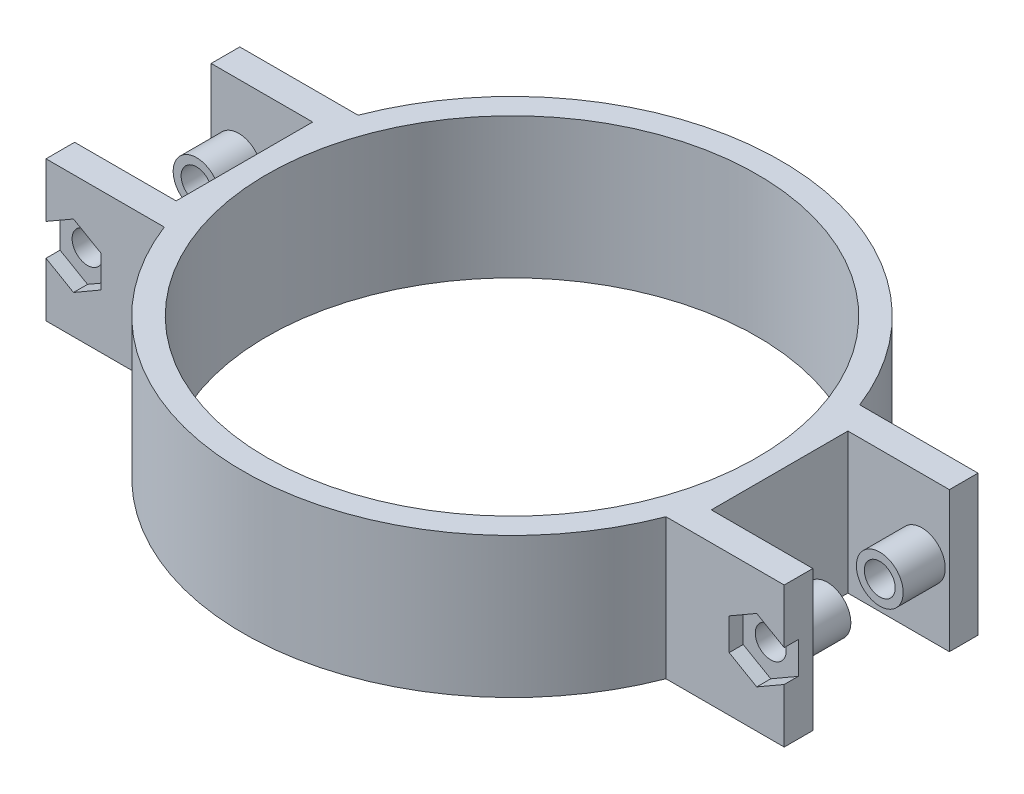
SolidWorks part; units mm, degrees
ref_plane "前视基准面" through (0, 0, 0) normal (0, 0, 1) x (1, 0, 0)
ref_plane "上视基准面" through (0, 0, 0) normal (0, 1, 0) x (1, 0, 0)
ref_plane "右视基准面" through (0, 0, 0) normal (1, 0, 0) x (0, 0, -1)
sketch "草图1" plane through (0, 0, 0) normal (0, 1, 0) x (1, 0, 0)
  line L0 (-39.4388, 7.2962) -> (-28.5931, 7.2962)
  line L1 (-26.8011, -10.3527) -> (-39.4388, -10.3527)
  line L2 (-28.5931, 7.2962) -> (-28.5931, -7.2962)
  line L3 (-26.8011, 10.3527) -> (-39.4388, 10.3527)
  line L4 (-39.4388, -10.3527) -> (-39.4388, -7.2962)
  line L5 (-28.5931, -7.2962) -> (-39.4388, -7.2962)
  line L6 (-39.4388, 7.2962) -> (-39.4388, 10.3527)
  line L7 (26.8011, 10.3527) -> (39.4388, 10.3527)
  line L8 (39.4388, 10.3527) -> (39.4388, 7.2962)
  line L9 (39.4388, -10.3527) -> (26.8011, -10.3527)
  line L10 (39.4388, -7.2962) -> (39.4388, -10.3527)
  line L11 (39.4388, 7.2962) -> (28.5931, 7.2962)
  line L12 (28.5931, 7.2962) -> (28.5931, -7.2962)
  line L13 (28.5931, -7.2962) -> (39.4388, -7.2962)
  circle A0 centre (0, 0) radius 26.2
  arc A2 (-26.8011, -10.3527) -> (26.8011, -10.3527) centre (0, 0) ccw
  arc A3 (26.8011, 10.3527) -> (-26.8011, 10.3527) centre (0, 0) ccw
  dimension "D1" = 52.4
extrude "凸台-拉伸1" add sketch "草图1" along normal blind 15
sketch "草图2" plane through (0, 0, -10.3527) normal (0, 0, -1) x (-1, 0, 0)
  circle A0 centre (36.5, 7.5) radius 1.65
  circle A1 centre (-36.5, 7.5) radius 1.65
extrude "切除-拉伸1" cut sketch "草图2" against normal blind 23
sketch "草图3" plane through (0, 0, 10.3527) normal (0, 0, 1) x (1, 0, 0)
  line L1 (-36.5, 4.1) -> (-33.5555, 5.8)
  line L2 (-33.5555, 5.8) -> (-33.5555, 9.2)
  line L3 (-33.5555, 9.2) -> (-36.5, 10.9)
  line L4 (-36.5, 10.9) -> (-39.4445, 9.2)
  line L5 (-39.4445, 9.2) -> (-39.4445, 5.8)
  line L6 (-39.4445, 5.8) -> (-36.5, 4.1)
  circle A0 centre (-36.5, 7.5) radius 2.9445 construction
  dimension "D1" = 3.4
extrude "切除-拉伸2" cut sketch "草图3" against normal blind 1.5
sketch "草图4" plane through (0, 0, 10.3527) normal (0, 0, 1) x (1, 0, 0)
  line L1 (36.5, 4.1) -> (39.4445, 5.8)
  line L2 (39.4445, 5.8) -> (39.4445, 9.2)
  line L3 (39.4445, 9.2) -> (36.5, 10.9)
  line L4 (36.5, 10.9) -> (33.5555, 9.2)
  line L5 (33.5555, 9.2) -> (33.5555, 5.8)
  line L6 (33.5555, 5.8) -> (36.5, 4.1)
  circle A0 centre (36.5, 7.5) radius 2.9445 construction
  dimension "D1" = 3.4
extrude "切除-拉伸3" cut sketch "草图4" against normal blind 1.5
sketch "草图5" plane through (0, 0, -7.2962) normal (0, 0, 1) x (1, 0, 0)
  circle A0 centre (-36.5, 7.5) radius 2.5
  circle A1 centre (-36.5, 7.5) radius 1.65
  dimension "D1" = 5
extrude "凸台-拉伸2" add sketch "草图5" along normal blind 4.5
sketch "草图6" plane through (0, 0, 7.2962) normal (0, 0, -1) x (-1, 0, 0)
  circle A0 centre (36.5, 7.5) radius 1.65
  circle A1 centre (36.5, 7.5) radius 2.5
  dimension "D1" = 5
extrude "凸台-拉伸3" add sketch "草图6" along normal blind 4.5
sketch "草图7" plane through (0, 0, -7.2962) normal (0, 0, 1) x (1, 0, 0)
  circle A0 centre (36.5, 7.5) radius 1.65
  circle A1 centre (36.5, 7.5) radius 2.5
  dimension "D1" = 5
extrude "凸台-拉伸4" add sketch "草图7" along normal blind 4.5
sketch "草图8" plane through (0, 0, 7.2962) normal (0, 0, -1) x (-1, 0, 0)
  circle A0 centre (-36.5, 7.5) radius 1.65
  circle A1 centre (-36.5, 7.5) radius 2.5
  dimension "D1" = 5
extrude "凸台-拉伸5" add sketch "草图8" along normal blind 4.5
